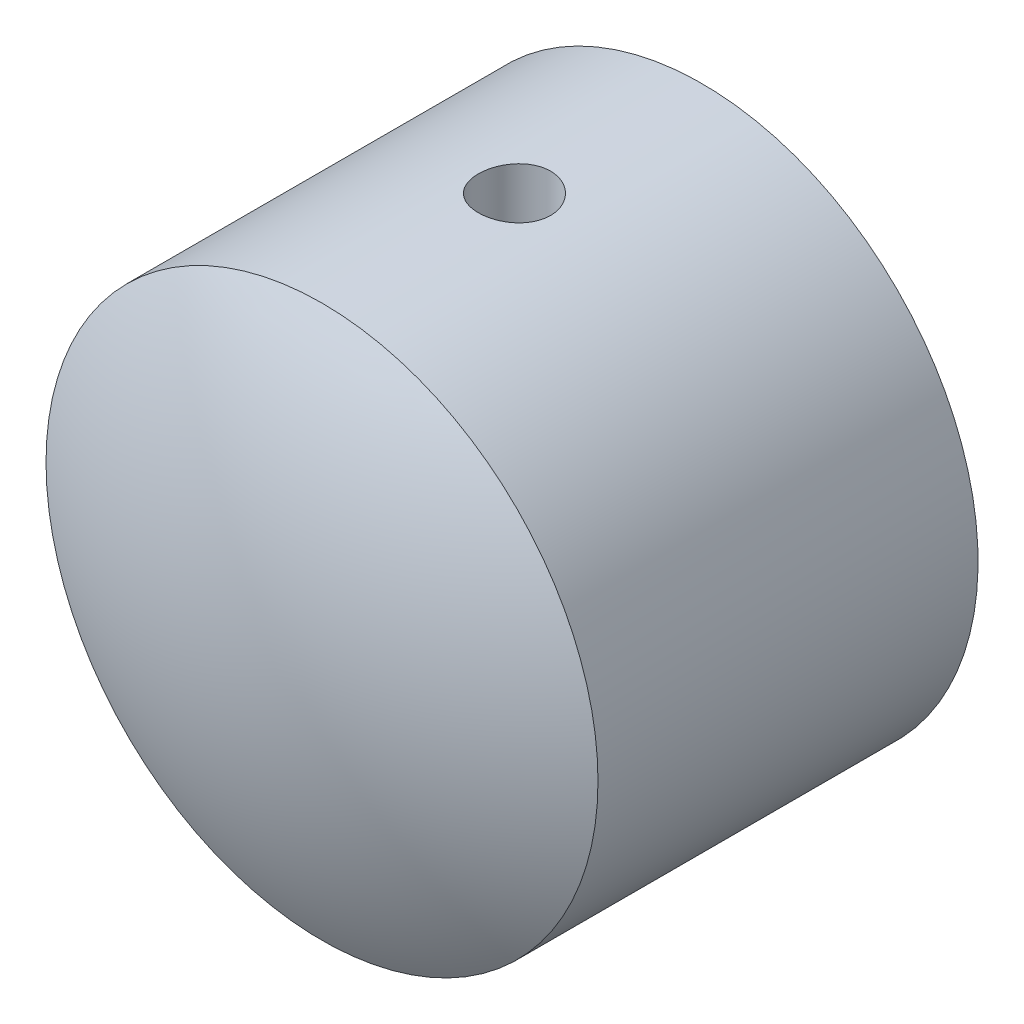
SolidWorks part; units mm, degrees
ref_plane "Front Plane" through (0, 0, 0) normal (0, 0, 1) x (1, 0, 0)
ref_plane "Top Plane" through (0, 0, 0) normal (0, 1, 0) x (1, 0, 0)
ref_plane "Right Plane" through (0, 0, 0) normal (1, 0, 0) x (0, 0, -1)
sketch "Sketch1" plane through (0, 0, 0) normal (0, 0, 1) x (1, 0, 0)
  circle A0 centre (67.1145, 307.3271) radius 36.4268
extrude "Boss-Extrude1" add sketch "Sketch1" against normal blind 2.54 and the other way blind 47.625 contours A0
sketch "Sketch2" plane through (0, 0, 47.625) normal (0, 0, 1) x (1, 0, 0)
  circle A0 centre (67.1145, 307.3271) radius 36.4268 construction
  point P0 (67.1145, 343.7539)
ref_plane "Plane1" through (67.1145, 0, 0) normal (1, 0, 0) x (0, 0, -1)
sketch "Sketch3" plane through (67.1145, 0, 0) normal (1, 0, 0) x (0, 0, -1)
  line L0 (-47.625, 307.3271) -> (-57.15, 307.3271)
  line L1 (-47.625, 343.7539) -> (-47.625, 270.9004) construction
  line L3 (2.54, 307.3271) -> (12.065, 307.3271)
  line L4 (2.54, 270.9004) -> (2.54, 343.7539) construction
  line L5 (-47.625, 343.7539) -> (-47.625, 307.3271)
  line L6 (2.54, 307.3271) -> (2.54, 343.7539)
  arc A0 (-47.625, 343.7539) -> (-57.15, 307.3271) centre (17.2665, 307.3271) ccw
  arc A1 (2.54, 343.7539) -> (12.065, 307.3271) centre (-62.3515, 307.3271) cw
  dimension "D1" = 9.525
  dimension "D2" = 9.525
revolve "Revolve1" add sketch "Sketch3" angle 360 about L0
ref_plane "Plane2" through (0, 343.7539, 0) normal (0, 1, 0) x (1, 0, 0)
sketch "Sketch4" plane through (0, 343.7539, 0) normal (0, 1, 0) x (1, 0, 0)
  circle A0 centre (67.1145, -22.225) radius 4.7625
extrude "Cut-Extrude1" cut sketch "Sketch4" against normal through all contours A0
